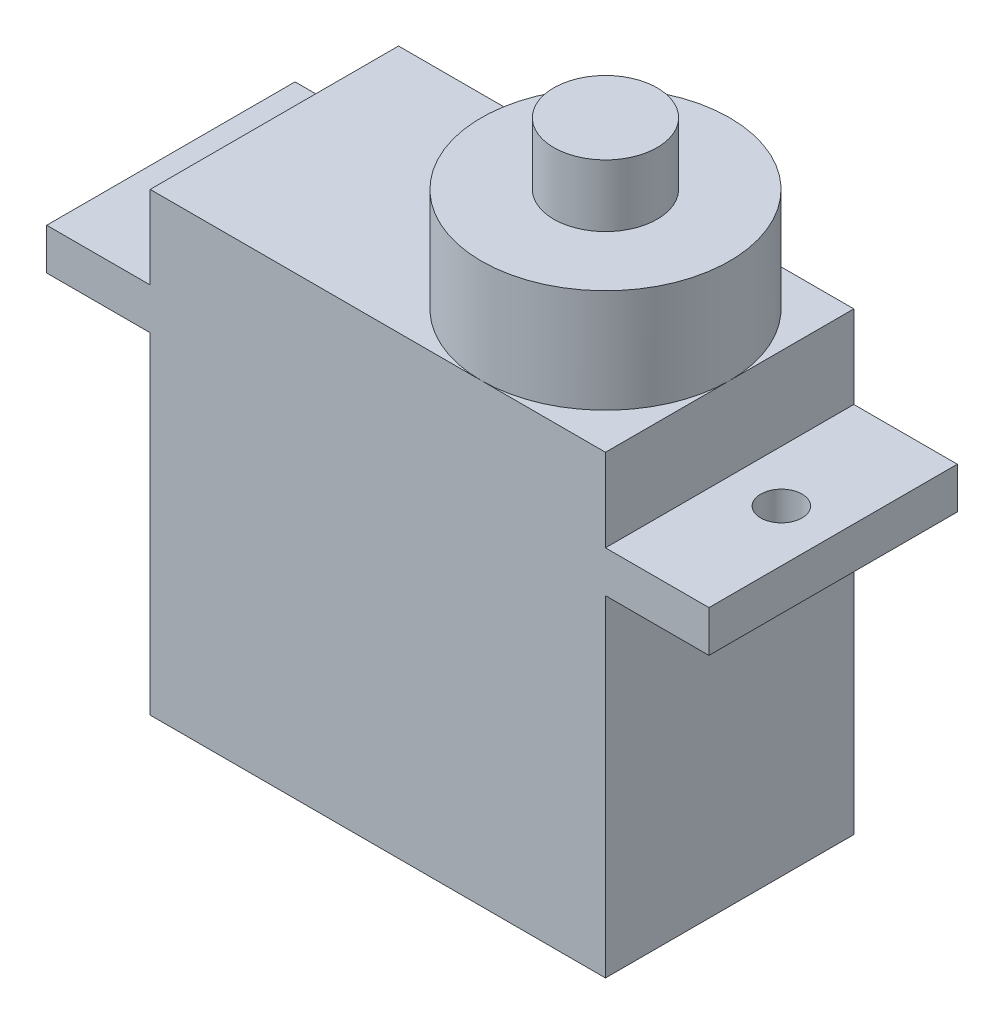
SolidWorks part; units mm, degrees
ref_plane "Front Plane" through (0, 0, 0) normal (0, 0, 1) x (1, 0, 0)
ref_plane "Top Plane" through (0, 0, 0) normal (0, 1, 0) x (1, 0, 0)
ref_plane "Right Plane" through (0, 0, 0) normal (1, 0, 0) x (0, 0, -1)
sketch "Sketch1" plane through (0, 0, 0) normal (0, 1, 0) x (1, 0, 0)
  line L1 (0, 0) -> (22, 0)
  line L2 (0, 0) -> (0, 12)
  line L3 (0, 12) -> (22, 12)
  line L4 (22, 0) -> (22, 12)
  dimension "D1" = 22
  dimension "D2" = 12
extrude "Boss-Extrude1" add sketch "Sketch1" along normal blind 22
sketch "Sketch2" plane through (0, 0, 0) normal (0, 0, 1) x (1, 0, 0)
  line L0 (0, 0) -> (22, 0) construction
  line L1 (-5, 18) -> (27, 18)
  line L2 (-5, 18) -> (-5, 16)
  line L3 (-5, 16) -> (27, 16)
  line L4 (27, 18) -> (27, 16)
  dimension "D1" = 32
  dimension "D2" = 2
  dimension "D3" = 5
  dimension "D4" = 16
extrude "Boss-Extrude2" add sketch "Sketch2" against normal through all
sketch "Sketch3" plane through (0, 18, 0) normal (0, 1, 0) x (1, 0, 0)
  line L0 (-5, 12) -> (-5, 0) construction
  line L1 (0, 0) -> (-5, 0) construction
  line L2 (27, 12) -> (27, 0) construction
  line L3 (27, 0) -> (22, 0) construction
  circle A0 centre (-2.5, 6) radius 1
  circle A1 centre (24.5, 6) radius 1
  point P4 (-5, 6)
  point P9 (27, 6)
  point P12 (24.5, 0)
  dimension "D1" = 2
  dimension "D2" = 2
  dimension "D3" = 2.5
  dimension "D4" = 6
  dimension "D5" = 2.5
  dimension "D6" = 6
extrude "Cut-Extrude1" cut sketch "Sketch3" against normal blind 22
sketch "Sketch5" plane through (0, 22, 0) normal (0, 1, 0) x (1, 0, 0)
  line L0 (22, 6) -> (16, 6) construction
  line L1 (22, 0) -> (22, 12) construction
  circle A0 centre (16, 6) radius 6
  dimension "D1" = 6
extrude "Boss-Extrude3" add sketch "Sketch5" along normal blind 5
sketch "Sketch6" plane through (0, 27, 0) normal (0, 1, 0) x (1, 0, 0)
  circle A0 centre (16, 6) radius 2.5
  dimension "D1" = 5
extrude "Boss-Extrude4" add sketch "Sketch6" along normal blind 3
